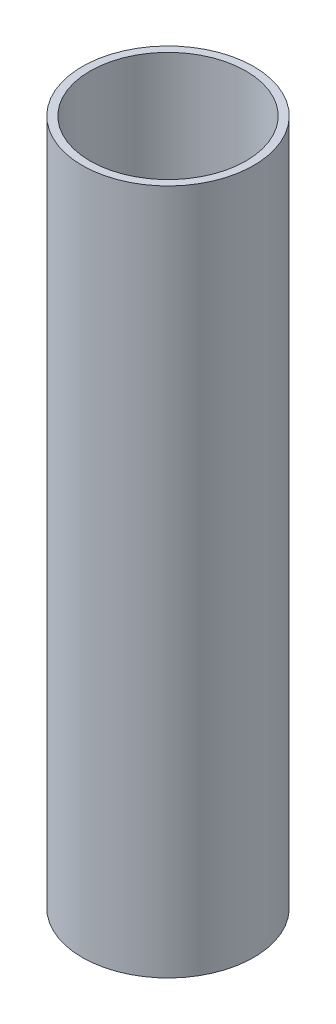
SolidWorks part; units mm, degrees
material "ASTM A36 Steel"
ref_plane "Front Plane" through (0, 0, 0) normal (0, 0, 1) x (1, 0, 0)
ref_plane "Top Plane" through (0, 0, 0) normal (0, 1, 0) x (1, 0, 0)
ref_plane "Right Plane" through (0, 0, 0) normal (1, 0, 0) x (0, 0, -1)
sketch "Sketch1" plane through (0, 0, 0) normal (0, 1, 0) x (1, 0, 0)
  circle A0 centre (0, 0) radius 11
  circle A1 centre (0, 0) radius 10
extrude "Boss-Extrude1" add sketch "Sketch1" along normal blind 88
